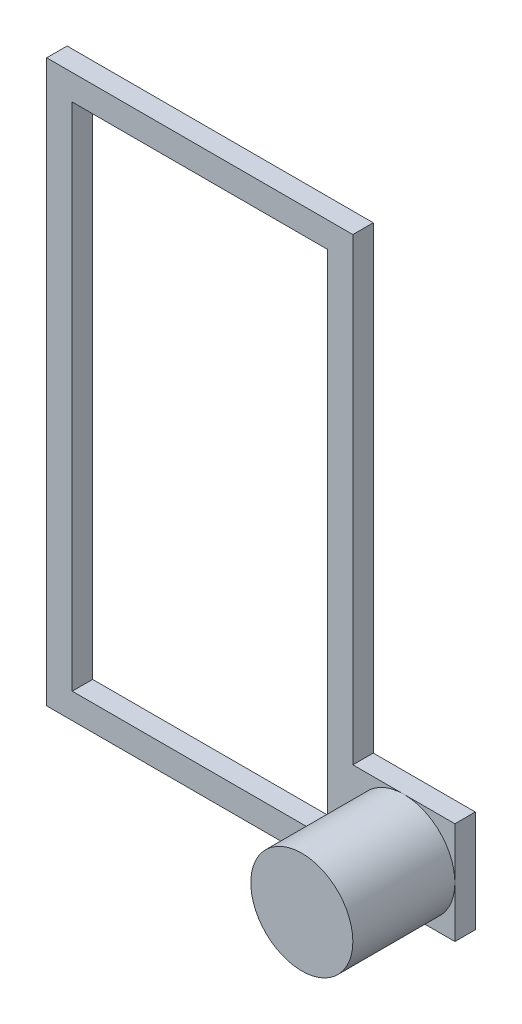
SolidWorks part; units mm, degrees
ref_plane "Front Plane" through (0, 0, 0) normal (0, 0, 1) x (1, 0, 0)
ref_plane "Top Plane" through (0, 0, 0) normal (0, 1, 0) x (1, 0, 0)
ref_plane "Right Plane" through (0, 0, 0) normal (1, 0, 0) x (0, 0, -1)
sketch "Sketch1" plane through (0, 0, 0) normal (0, 0, 1) x (1, 0, 0)
  line L0 (19.05, -34.925) -> (19.05, -22.225) construction
  line L1 (-19.05, -34.925) -> (19.05, -34.925)
  line L2 (-19.05, -34.925) -> (-19.05, 34.925)
  line L3 (-19.05, 34.925) -> (19.05, 34.925)
  line L4 (19.05, -22.225) -> (19.05, 34.925)
  line L5 (-19.05, -34.925) -> (19.05, 34.925) construction
  line L6 (-19.05, 34.925) -> (19.05, -34.925) construction
  line L11 (19.05, -34.925) -> (31.75, -34.925)
  line L13 (19.05, -22.225) -> (31.75, -22.225)
  line L14 (31.75, -34.925) -> (31.75, -22.225)
  point P0 (0, 0)
  point P6 (0, 0)
  dimension "D1" = 38.1
  dimension "D2" = 69.85
  dimension "D3" = 12.7
  dimension "D4" = 12.7
extrude "Boss-Extrude1" add sketch "Sketch1" along normal blind 2.54 contours L3 L4 L13 L14 L11 L1 L2
sketch "Sketch2" plane through (0, 0, 2.54) normal (0, 0, 1) x (1, 0, 0)
  line L1 (-15.875, -31.75) -> (15.875, -31.75)
  line L2 (-15.875, -31.75) -> (-15.875, 31.75)
  line L3 (-15.875, 31.75) -> (15.875, 31.75)
  line L4 (15.875, -31.75) -> (15.875, 31.75)
  line L5 (-15.875, -31.75) -> (15.875, 31.75) construction
  line L6 (-15.875, 31.75) -> (15.875, -31.75) construction
  point P0 (0, 0)
  dimension "D1" = 63.5
  dimension "D2" = 31.75
extrude "Cut-Extrude1" cut sketch "Sketch2" against normal through all
sketch "Sketch3" plane through (0, 0, 2.54) normal (0, 0, 1) x (1, 0, 0)
  line L0 (31.75, -34.925) -> (31.75, -22.225) construction
  line L1 (19.05, -22.225) -> (31.75, -22.225) construction
  line L2 (-19.05, -34.925) -> (31.75, -34.925) construction
  circle A0 centre (25.4, -28.575) radius 6.35
extrude "Boss-Extrude2" add sketch "Sketch3" along normal blind 12.7
